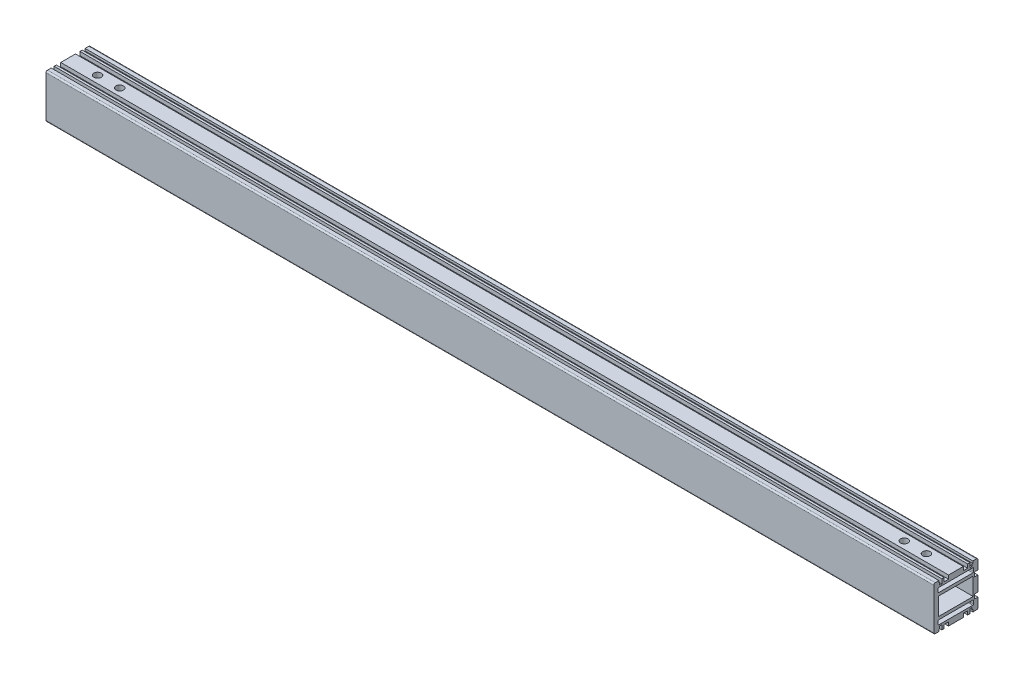
SolidWorks part; units mm, degrees
ref_plane "前视基准面" through (0, 0, 0) normal (0, 0, 1) x (1, 0, 0)
ref_plane "上视基准面" through (0, 0, 0) normal (0, 1, 0) x (1, 0, 0)
ref_plane "右视基准面" through (0, 0, 0) normal (1, 0, 0) x (0, 0, -1)
sketch "草图1" plane through (0, 0, 0) normal (1, 0, 0) x (0, 0, -1)
  line L0 (-15, 15) -> (15, -15) construction
  line L1 (-14, 15) -> (-11.5, 15)
  line L2 (-15, 14) -> (-15, -14)
  line L3 (-14, -15) -> (-11.5, -15)
  line L4 (15, 14) -> (15, 8)
  line L5 (15, 15) -> (-15, -15) construction
  line L6 (-11.5, 15) -> (-11.5, 13.5)
  line L7 (-11.5, 13.5) -> (-11.4, 13.5)
  line L8 (-11, 13.1) -> (-11, 12)
  line L9 (-11, 12) -> (-9.5, 12)
  line L10 (-9.5, 12) -> (-9.5, 15)
  line L11 (-9.5, 15) -> (-8, 15)
  line L12 (-8, 15) -> (-8, 12.5)
  line L13 (-8, 12.5) -> (-5, 12.5)
  line L14 (-5, 12.5) -> (-5, 15)
  line L15 (-5, 15) -> (5, 15)
  line L16 (0, 21.5201) -> (0, -18.309) construction
  line L17 (0, 55) -> (0, -55) construction
  line L18 (5, 12.5) -> (5, 15)
  line L19 (8, 12.5) -> (5, 12.5)
  line L20 (8, 15) -> (8, 12.5)
  line L21 (9.5, 15) -> (8, 15)
  line L22 (9.5, 12) -> (9.5, 15)
  line L23 (11, 12) -> (9.5, 12)
  line L24 (11, 13.1) -> (11, 12)
  line L25 (11.5, 13.5) -> (11.4, 13.5)
  line L26 (11.5, 15) -> (11.5, 13.5)
  line L27 (8, 15) -> (9.5, 15)
  line L28 (11.5, 15) -> (14, 15)
  line L29 (-19.8303, 0) -> (22.13, 0) construction
  line L30 (55, 0) -> (-55, 0) construction
  line L31 (8, -15) -> (9.5, -15)
  line L32 (11.5, -15) -> (11.5, -13.5)
  line L33 (11.5, -13.5) -> (11.4, -13.5)
  line L34 (11, -13.1) -> (11, -12)
  line L35 (11, -12) -> (9.5, -12)
  line L36 (9.5, -12) -> (9.5, -15)
  line L37 (9.5, -15) -> (8, -15)
  line L38 (8, -15) -> (8, -12.5)
  line L39 (8, -12.5) -> (5, -12.5)
  line L40 (5, -12.5) -> (5, -15)
  line L41 (-5, -15) -> (5, -15)
  line L42 (-5, -12.5) -> (-5, -15)
  line L43 (-8, -12.5) -> (-5, -12.5)
  line L44 (-8, -15) -> (-8, -12.5)
  line L45 (-9.5, -15) -> (-8, -15)
  line L46 (-9.5, -12) -> (-9.5, -15)
  line L47 (-11, -12) -> (-9.5, -12)
  line L48 (-11, -13.1) -> (-11, -12)
  line L49 (-11.5, -13.5) -> (-11.4, -13.5)
  line L50 (-11.5, -15) -> (-11.5, -13.5)
  line L51 (-9.5, -15) -> (-8, -15)
  line L52 (-5, -15) -> (5, -15)
  line L53 (8, -15) -> (9.5, -15)
  line L54 (11.5, -15) -> (14, -15)
  line L55 (15, 8) -> (12.5, 8)
  line L56 (12.5, 8) -> (12.5, 5)
  line L57 (12.5, 5) -> (15, 5)
  line L58 (12.5, -5) -> (15, -5)
  line L59 (12.5, -8) -> (12.5, -5)
  line L60 (15, -8) -> (12.5, -8)
  line L61 (15, 5) -> (15, -5)
  line L62 (15, -8) -> (15, -14)
  line L63 (12, -10.5) -> (12, -8.5)
  line L64 (-11.5, 11) -> (11.5, 11)
  line L65 (-12, 10.5) -> (-12, 8.5)
  line L66 (-11.5, 8) -> (11.5, 8)
  line L67 (12, 10.5) -> (12, 8.5)
  line L68 (-11.5, -8) -> (11.5, -8)
  line L69 (-12, -10.5) -> (-12, -8.5)
  line L70 (-11.5, -11) -> (11.5, -11)
  line L72 (-11.75, 6) -> (11.75, 6)
  line L73 (-11.75, 6) -> (-11.75, -6)
  line L74 (-11.75, -6) -> (11.75, -6)
  line L75 (11.75, 6) -> (11.75, -6)
  arc A0 (12, 8.5) -> (11.5, 8) centre (11.5, 8.5) cw
  arc A1 (11.5, 11) -> (12, 10.5) centre (11.5, 10.5) cw
  arc A2 (-11.5, 11) -> (-12, 10.5) centre (-11.5, 10.5) ccw
  arc A3 (-11.5, 8) -> (-12, 8.5) centre (-11.5, 8.5) cw
  arc A4 (-11, -13.1) -> (-11.4, -13.5) centre (-11.4, -13.1) cw
  arc A5 (11.4, -13.5) -> (11, -13.1) centre (11.4, -13.1) cw
  arc A6 (11.4, 13.5) -> (11, 13.1) centre (11.4, 13.1) ccw
  arc A7 (-11, 13.1) -> (-11.4, 13.5) centre (-11.4, 13.1) ccw
  arc A8 (-11.5, -8) -> (-12, -8.5) centre (-11.5, -8.5) ccw
  arc A9 (-11.5, -11) -> (-12, -10.5) centre (-11.5, -10.5) cw
  arc A10 (11.5, -11) -> (12, -10.5) centre (11.5, -10.5) ccw
  arc A11 (12, -8.5) -> (11.5, -8) centre (11.5, -8.5) ccw
  arc A12 (14, 15) -> (15, 14) centre (14, 14) cw
  arc A13 (14, -15) -> (15, -14) centre (14, -14) ccw
  arc A14 (-15, -14) -> (-14, -15) centre (-14, -14) ccw
  arc A15 (-15, 14) -> (-14, 15) centre (-14, 14) cw
  point P69 (12, 11)
  point P72 (-12, 11)
  point P77 (-11, -13.5)
  point P80 (11, -13.5)
  point P83 (11, 13.5)
  point P86 (-11, 13.5)
  point P99 (-12, -11)
  point P100 (12, -11)
  dimension "D17" = 0.5
  dimension "D18" = 0.4
  dimension "D21" = 1
  dimension "D1" = 3.5
  dimension "D2" = 1.5
  dimension "D3" = 0.5
  dimension "D4" = 1.5
  dimension "D5" = 3
  dimension "D6" = 30
  dimension "D7" = 30
  dimension "D8" = 1.5
  dimension "D9" = 2.5
  dimension "D10" = 3
  dimension "D11" = 2.5
  dimension "D12" = 7
  dimension "D13" = 3
  dimension "D14" = 4
  dimension "D15" = 3
  dimension "D16" = 24
  dimension "D19" = 23.5
  dimension "D20" = 12
extrude "凸台-拉伸1" add sketch "草图1" along normal mid plane 602 contours A15 L2 A14 L3 L50 L49 A4 L48 L47 L46 L45 L44 L43 L42 L41 L40 L39 L38 L31 L36 L35 L34 A5 L33 L32 L54 A13 L62 L60 L59 L58 L61 L57 L56 L55 L4 A12 L28 L26 L25 A6 L24 L23 L22 L21 L20 L19 L18 L15 L14 L13
hole_wizard "M6 螺纹孔1" positions "草图3" profile "草图2" tap size "M6" standard "GB"
sketch "草图3" plane through (0, 0, -15) normal (0, 0, -1) x (-1, 0, 0)
  line L0 (-301, 5) -> (-301, -5) construction
  line L1 (-301, -15) -> (301, -15) construction
  point P0 (-281, 0)
  point P1 (-266, 0)
  point P4 (29, 0)
  point P7 (14, 0)
  point P10 (99, 0)
  point P13 (114, 0)
  dimension "D1" = 20
  dimension "D2" = 15
sketch "草图2" plane through (281, 0, -15) normal (1, 0, 0) x (0, 1, 0)
  line L0 (0, 0) -> (0, 16.5022)
  line L1 (0, 16.5022) -> (2.5, 15)
  line L2 (2.5, 15) -> (2.5, 0)
  line L5 (2.5, 0) -> (0, 0)
  line L10 (0, 16.5022) -> (-2.5, 15) construction
  line L11 (0, -6.35) -> (0, 107.95) construction
  dimension "螺纹孔钻头直径" = 5
  dimension "螺纹孔钻头深度" = 15
  dimension "导头角度" = 118
cosmetic thread "孔螺蚊线1" parameters "D1"=3.25, "D2"=6
cosmetic thread "孔螺蚊线2" parameters "D1"=3.25, "D2"=6
cosmetic thread "孔螺蚊线3" parameters "D1"=3.25, "D2"=6
cosmetic thread "孔螺蚊线4" parameters "D1"=3.25, "D2"=6
cosmetic thread "孔螺蚊线5" parameters "D1"=3.25, "D2"=6
cosmetic thread "孔螺蚊线6" parameters "D1"=3.25, "D2"=6
hole_wizard "M6 螺纹孔2" positions "草图5" profile "草图4" tap size "M6" standard "GB"
sketch "草图5" plane through (0, 15, 0) normal (0, 1, 0) x (-1, 0, 0)
  line L0 (301, 5) -> (301, -5) construction
  line L1 (-301, 15) -> (301, 15) construction
  point P0 (281, 0)
  point P1 (266, 0)
  point P4 (-266, 0)
  point P7 (-281, 0)
  dimension "D1" = 20
  dimension "D2" = 15
sketch "草图4" plane through (-281, 15, 0) normal (1, 0, 0) x (0, 0, 1)
  line L0 (0, 0) -> (0, 16.5022)
  line L1 (0, 16.5022) -> (2.5, 15)
  line L2 (2.5, 15) -> (2.5, 0)
  line L5 (2.5, 0) -> (0, 0)
  line L10 (0, 16.5022) -> (-2.5, 15) construction
  line L11 (0, -6.35) -> (0, 107.95) construction
  dimension "螺纹孔钻头直径" = 5
  dimension "螺纹孔钻头深度" = 15
  dimension "导头角度" = 118
cosmetic thread "孔螺蚊线7" parameters "D1"=9, "D2"=6
cosmetic thread "孔螺蚊线8" parameters "D1"=9, "D2"=6
cosmetic thread "孔螺蚊线9" parameters "D1"=9, "D2"=6
cosmetic thread "孔螺蚊线10" parameters "D1"=9, "D2"=6
hole_wizard "M4 螺纹孔1" positions "草图7" profile "草图6" tap size "M4" standard "GB"
sketch "草图7" plane through (0, 0, -15) normal (0, 0, -1) x (-1, 0, 0)
  line L0 (-301, -15) -> (301, -15) construction
  line L1 (-301, -8) -> (-301, -14) construction
  point P1 (-96, 0)
  point P3 (-231, 0)
  dimension "D1" = 135
  dimension "D2" = 15
  dimension "D3" = 15
  dimension "D4" = 70
sketch "草图6" plane through (96, 0, -15) normal (1, 0, 0) x (0, 1, 0)
  line L0 (0, 0) -> (0, 11.0914)
  line L1 (0, 11.0914) -> (1.65, 10.1)
  line L2 (1.65, 10.1) -> (1.65, 0)
  line L5 (1.65, 0) -> (0, 0)
  line L10 (0, 11.0914) -> (-1.65, 10.1) construction
  line L11 (0, -6.35) -> (0, 107.95) construction
  dimension "螺纹孔钻头直径" = 3.3
  dimension "螺纹孔钻头深度" = 10.1
  dimension "导头角度" = 118
cosmetic thread "孔螺蚊线11" parameters "D1"=3.25, "D2"=4
cosmetic thread "孔螺蚊线12" parameters "D1"=3.25, "D2"=4
